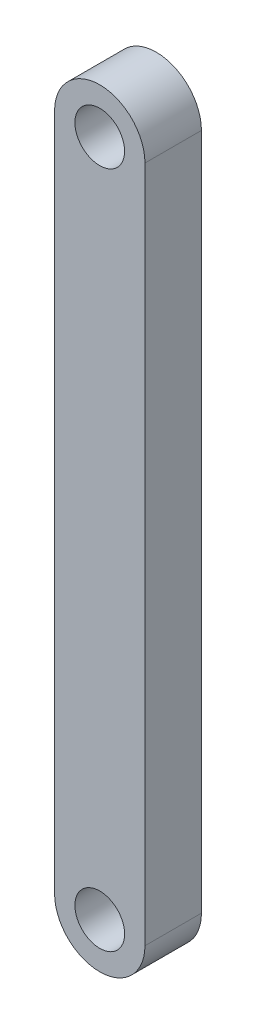
SolidWorks part; units mm, degrees
ref_plane "Front Plane" through (0, 0, 0) normal (0, 0, 1) x (1, 0, 0)
ref_plane "Top Plane" through (0, 0, 0) normal (0, 1, 0) x (1, 0, 0)
ref_plane "Right Plane" through (0, 0, 0) normal (1, 0, 0) x (0, 0, -1)
sketch "Sketch1" plane through (0, 0, 0) normal (0, 0, 1) x (1, 0, 0)
  line L6 (-4, 60) -> (-4, 0)
  line L8 (4, 60) -> (4, 0)
  circle A0 centre (0, 0) radius 2.2
  circle A1 centre (0, 60) radius 2.2
  arc A4 (4, 60) -> (-4, 60) centre (0, 60) ccw
  arc A5 (-4, 0) -> (4, 0) centre (0, 0) ccw
  dimension "D2" = 4.4
  dimension "D3" = 4.4
  dimension "D4" = 8
  dimension "D5" = 8
  dimension "D1" = 60
extrude "Boss-Extrude1" add sketch "Sketch1" along normal blind 5
